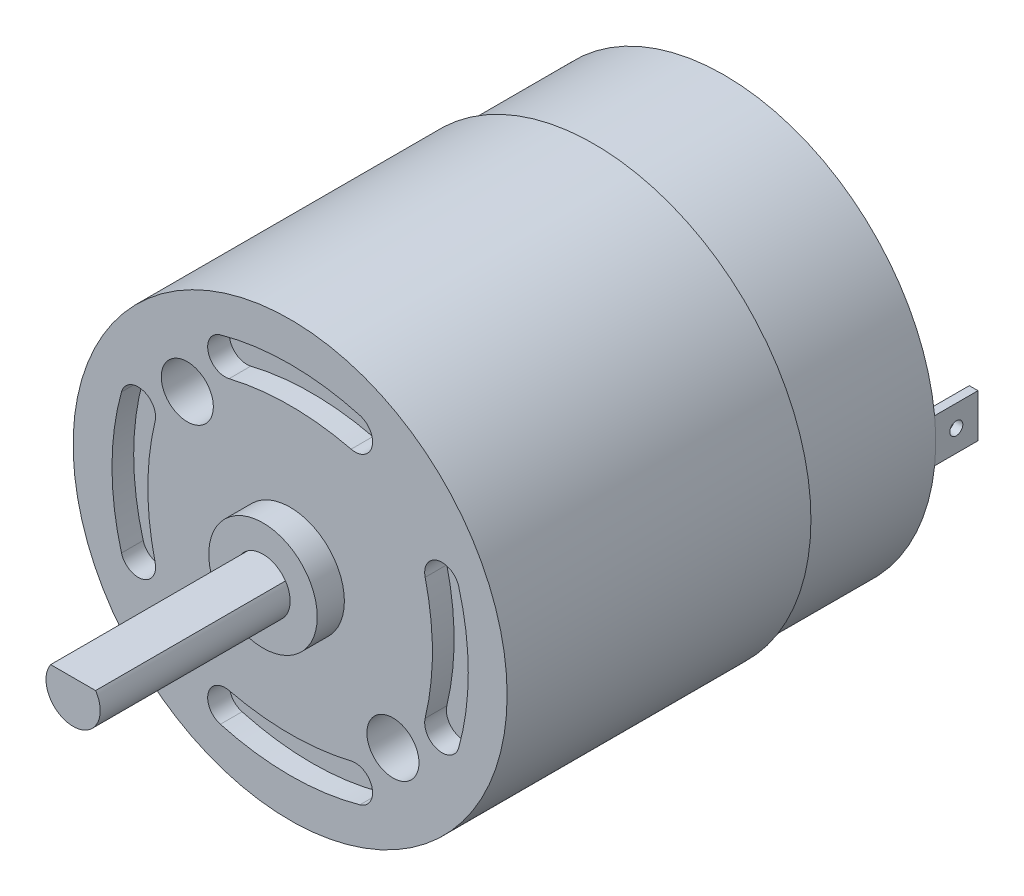
SolidWorks part; units mm, degrees
ref_plane "Front Plane" through (0, 0, 0) normal (0, 0, 1) x (1, 0, 0)
ref_plane "Top Plane" through (0, 0, 0) normal (0, 1, 0) x (1, 0, 0)
ref_plane "Right Plane" through (0, 0, 0) normal (1, 0, 0) x (0, 0, -1)
sketch "Sketch2" plane through (0, 0, 0) normal (0, 0, 1) x (1, 0, 0)
  circle A0 centre (0, 0) radius 12.7
  dimension "D1" = 25.4
extrude "Boss-Extrude1" add sketch "Sketch2" against normal mid plane 25.4
sketch "Sketch3" plane through (0, 0, 12.7) normal (0, 0, 1) x (1, 0, 0)
  circle A0 centre (0, 0) radius 3.175
  circle A2 centre (0, 0) radius 1.5875
  dimension "D1" = 6.35
  dimension "D2" = 3.175
extrude "Boss-Extrude2" add sketch "Sketch3" along normal mid plane 3.175 contours A0 | A2
sketch "Sketch4" plane through (0, 0, 12.7) normal (0, 0, 1) x (1, 0, 0)
  circle A0 centre (0, 0) radius 1.5875
  dimension "D1" = 3.175
extrude "Boss-Extrude3" add sketch "Sketch4" along normal blind 12.7
sketch "Sketch5" plane through (0, 0, 25.4) normal (0, 0, 1) x (1, 0, 0)
  line L0 (-1.3152, 0.889) -> (1.3152, 0.889)
  circle A0 centre (0, 0) radius 1.5875 construction
  circle A1 centre (0, 0) radius 1.5875 construction
  arc A3 (-1.3152, 0.889) -> (1.3152, 0.889) centre (0, 0) cw
  dimension "D2" = 1.5875
  dimension "D1" = 0.889
extrude "Cut-Extrude1" cut sketch "Sketch5" against normal blind 12.7 contours A3 L0
sketch "Sketch6" plane through (0, 0, 12.7) normal (0, 0, 1) x (1, 0, 0)
  line L0 (-3.81, 8.89) -> (3.81, 8.89) construction
  line L1 (0, 8.89) -> (0, 0) construction
  arc A0 (-4.0821, 9.8689) -> (-3.5719, 7.9023) centre (-3.81, 8.89) ccw
  arc A1 (3.5719, 7.9023) -> (4.0821, 9.8689) centre (3.81, 8.89) ccw
  arc A2 (-3.5719, 7.9023) -> (3.5719, 7.9023) centre (0, -6.9132) cw
  arc A3 (-4.0821, 9.8689) -> (4.0821, 9.8689) centre (0, -4.8142) cw
  point P4 (0, 0)
  dimension "D1" = 2.032
  dimension "D2" = 15.24
  dimension "D3" = 3.81
  dimension "D4" = 8.89
extrude "Cut-Extrude2" cut sketch "Sketch6" against normal blind 1.27 contours A3 A1 A2 A0
pattern_circular "CirPattern1" count 4 over 360 about axis through (0, 0, 0) along (0, 0, 1) of "Cut-Extrude2"
sketch "Sketch7" plane through (0, 0, 12.7) normal (0, 0, 1) x (1, 0, 0)
  line L0 (-6.0168, 6.0168) -> (6.0168, -6.0168) construction
  line L1 (0, 0) -> (0, 8.3268) construction
  circle A0 centre (-6.0168, 6.0168) radius 1.524
  circle A1 centre (6.0168, -6.0168) radius 1.524
  arc A2 (3.5719, 7.9023) -> (-3.5719, 7.9023) centre (0, -6.9132) ccw construction
  point P4 (0, 0)
  dimension "D2" = 3.048
  dimension "D1" = 17.018
  dimension "D3" = 45
extrude "Cut-Extrude3" cut sketch "Sketch7" against normal blind 5.08 contours A0 | A1
sketch "Sketch8" plane through (0, 0, -12.7) normal (0, 0, -1) x (-1, 0, 0)
  circle A0 centre (0, 0) radius 12.3825
  circle A1 centre (0, 0) radius 12.7
  dimension "D1" = 24.765
  dimension "D2" = 25.4
extrude "Cut-Extrude4" cut sketch "Sketch8" against normal blind 7.62 contours A1 | A0
sketch "Sketch9" plane through (0, 0, -12.7) normal (0, 0, -1) x (-1, 0, 0)
  line L0 (-3.175, 0) -> (3.175, 0) construction
  circle A0 centre (-3.175, 0) radius 1.27
  circle A1 centre (3.175, 0) radius 1.27
  dimension "D1" = 2.54
  dimension "D2" = 6.35
extrude "Cut-Extrude5" cut sketch "Sketch9" against normal blind 2.54
ref_plane "Plane1" through (0, 0, -12.7) normal (0, 0, -1) x (-1, 0, 0)
sketch "Sketch11" plane through (0, 0, -12.7) normal (0, 0, -1) x (-1, 0, 0)
  line L0 (-11.8092, 1.27) -> (-11.8092, -1.27)
  line L1 (-12.3172, 1.27) -> (-11.8092, 1.27)
  line L2 (-12.3172, -1.27) -> (-11.8092, -1.27)
  line L3 (-12.3858, 0) -> (0, 0) construction
  line L4 (-12.3172, -1.27) -> (-12.3172, 1.27)
  circle A1 centre (0, 0) radius 12.3825 construction
  circle A2 centre (0, 0) radius 12.3825 construction
  point P10 (-11.8092, 0)
  dimension "D1" = 2.54
  dimension "D2" = 0.508
extrude "Boss-Extrude4" add sketch "Sketch11" along normal blind 2.54 contours L1 L0 L2 L4
sketch "Sketch12" plane through (12.3172, 0, 0) normal (1, 0, 0) x (0, 0, -1)
  line L0 (13.97, 1.27) -> (13.97, -1.27) construction
  line L1 (15.24, 1.27) -> (12.7, 1.27) construction
  line L2 (15.24, -1.27) -> (12.7, -1.27) construction
  circle A0 centre (13.97, 0) radius 0.381
  dimension "D1" = 0.762
extrude "Cut-Extrude6" cut sketch "Sketch12" against normal blind 2.54
mirror "Mirror1" about plane through (0, 0, 0) normal (1, 0, 0) of "Cut-Extrude6", "Boss-Extrude4"
